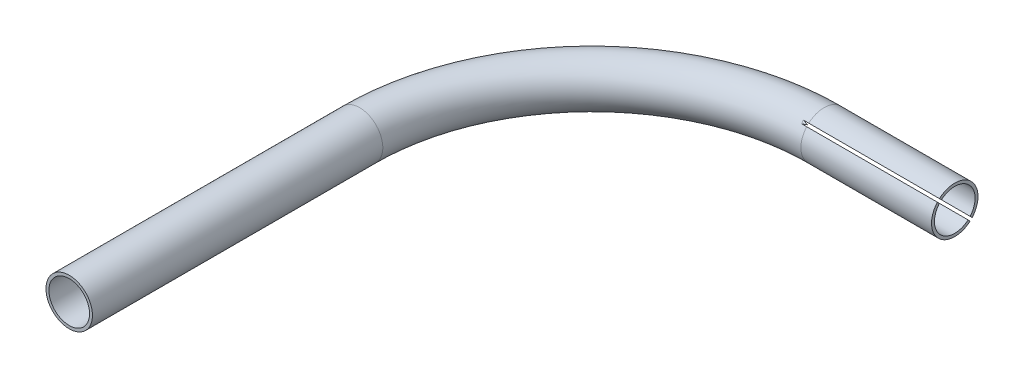
SolidWorks part; units mm, degrees
ref_plane "Спереди" through (0, 0, 0) normal (0, 0, 1) x (1, 0, 0)
ref_plane "Сверху" through (0, 0, 0) normal (0, 1, 0) x (1, 0, 0)
ref_plane "Справа" through (0, 0, 0) normal (1, 0, 0) x (0, 0, -1)
sketch "Эскиз1" plane through (0, 0, 0) normal (0, 1, 0) x (1, 0, 0)
  line L0 (-125, -180) -> (-125, -80)
  line L1 (0, 0) -> (-45, 0)
  line L2 (0, 0) -> (0, -87.0881) construction
  arc A0 (-125, -80) -> (-45, 0) centre (-45, -80) cw
  point P8 (0, 0)
  point P10 (0, 0)
  dimension "D1" = 80
  dimension "D2" = 125
  dimension "D3" = 180
sketch "Эскиз2" plane through (0, 0, 0) normal (1, 0, 0) x (0, 0, -1)
  circle A0 centre (0, 0) radius 8
  circle A1 centre (0, 0) radius 7
  dimension "D1" = 16
  dimension "D2" = 1
sweep "По траектории1" add profiles "Эскиз2" path "Эскиз1"
sketch "Эскиз3" plane through (0, 0, 0) normal (1, 0, 0) x (0, 0, -1)
  line L0 (0, 0) -> (-5.6569, 5.6569) construction
  line L1 (0, 0) -> (4.027, 0) construction
  line L2 (5.3033, -6.0104) -> (-6.0104, 5.3033)
  line L3 (5.3033, -6.0104) -> (6.0104, -5.3033)
  line L4 (-6.0104, 5.3033) -> (-5.3033, 6.0104)
  line L5 (6.0104, -5.3033) -> (-5.3033, 6.0104)
  line L6 (5.3033, -6.0104) -> (-5.3033, 6.0104) construction
  line L7 (-6.0104, 5.3033) -> (6.0104, -5.3033) construction
  circle A0 centre (0, 0) radius 8 construction
  dimension "D1" = 135
  dimension "D2" = 1
extrude "Вырез-Вытянуть1" cut sketch "Эскиз3" against normal blind 70
